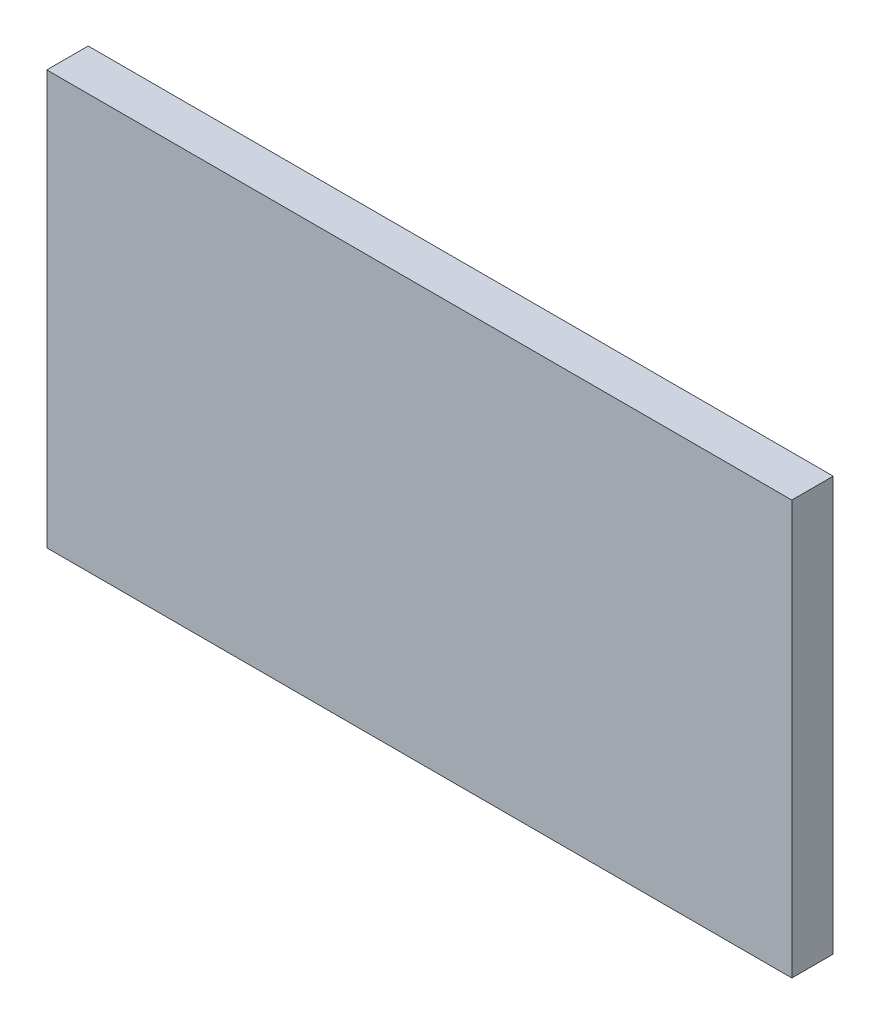
SolidWorks part; units mm, degrees
ref_plane "Front Plane" through (0, 0, 0) normal (0, 0, 1) x (1, 0, 0)
ref_plane "Top Plane" through (0, 0, 0) normal (0, 1, 0) x (1, 0, 0)
ref_plane "Right Plane" through (0, 0, 0) normal (1, 0, 0) x (0, 0, -1)
sketch "Sketch1" plane through (0, 0, 0) normal (0, 0, 1) x (1, 0, 0)
  line L0 (-57.15, 0) -> (57.15, 0)
  line L1 (57.15, 0) -> (57.15, 63.5)
  line L2 (57.15, 63.5) -> (-57.15, 63.5)
  line L3 (0, 63.5) -> (0, 0) construction
  line L4 (-57.15, 0) -> (-57.15, 63.5)
  dimension "D1" = 63.5
  dimension "D2" = 57.15
extrude "Boss-Extrude1" add sketch "Sketch1" along normal blind 6.35
